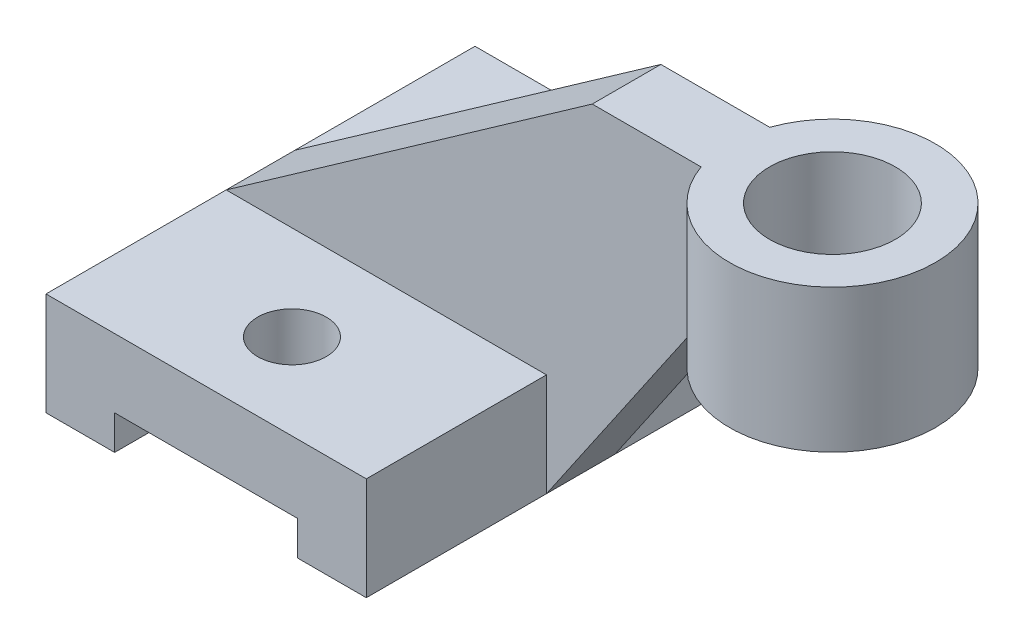
SolidWorks part; units mm, degrees
ref_plane "Ön Düzlem" through (0, 0, 0) normal (0, 0, 1) x (1, 0, 0)
ref_plane "Üst Düzlem" through (0, 0, 0) normal (0, 1, 0) x (1, 0, 0)
ref_plane "Sağ Düzlem" through (0, 0, 0) normal (1, 0, 0) x (0, 0, -1)
sketch "Sketch1" plane through (0, 0, 0) normal (0, 0, 1) x (1, 0, 0)
  line L0 (0, 0) -> (12, 0)
  line L1 (12, 0) -> (12, 6)
  line L2 (12, 6) -> (44, 6)
  line L3 (44, 6) -> (44, 0)
  line L4 (44, 0) -> (56, 0)
  line L5 (56, 0) -> (56, 18)
  line L6 (56, 18) -> (0, 18)
  line L7 (0, 18) -> (0, 0)
  dimension "D1" = 56
  dimension "D2" = 32
  dimension "D3" = 12
  dimension "D4" = 18
  dimension "D5" = 6
extrude "Boss-Extrude1" add sketch "Sketch1" against normal blind 75
sketch "Sketch2" plane through (0, 18, 0) normal (0, 1, 0) x (1, 0, 0)
  line L0 (56, 0) -> (0, 0) construction
  line L1 (56, 75) -> (56, 0) construction
  circle A0 centre (28, 15) radius 6
  circle A1 centre (28, 60) radius 6
  dimension "D3" = 12
  dimension "D4" = 12
  dimension "D1" = 45
  dimension "D2" = 15
  dimension "D5" = 28
extrude "Cut-Extrude1" cut sketch "Sketch2" against normal through all
ref_plane "Plane1" through (0, 0, -37.5) normal (0, 0, 1) x (1, 0, 0)
sketch "Sketch3" plane through (0, 0, -37.5) normal (0, 0, 1) x (1, 0, 0)
  line L0 (0, 18) -> (64, 63)
  line L1 (64, 63) -> (100, 63)
  line L2 (100, 63) -> (100, 38)
  line L3 (100, 38) -> (82, 38)
  line L4 (82, 38) -> (56, 0)
  line L5 (56, 0) -> (56, 18)
  line L6 (56, 18) -> (0, 18)
  dimension "D1" = 100
  dimension "D2" = 36
  dimension "D3" = 63
  dimension "D4" = 25
  dimension "D5" = 18
extrude "Boss-Extrude2" add sketch "Sketch3" along normal mid plane 12
sketch "Sketch4" plane through (0, 63, 0) normal (0, 1, 0) x (1, 0, 0)
  line L0 (100, 31.5) -> (100, 43.5) construction
  circle A0 centre (100, 37.5) radius 18
  dimension "D1" = 36
extrude "Boss-Extrude3" add sketch "Sketch4" against normal blind 25
sketch "Sketch5" plane through (0, 63, 0) normal (0, 1, 0) x (1, 0, 0)
  circle A0 centre (100, 37.5) radius 11
  dimension "D1" = 22
extrude "Cut-Extrude2" cut sketch "Sketch5" against normal through all
